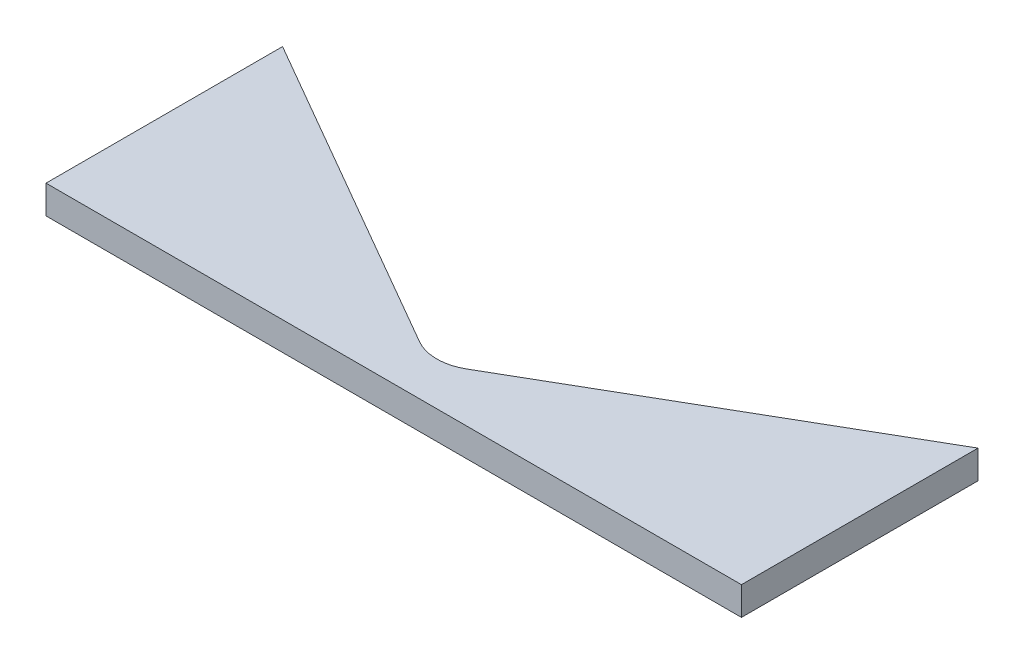
SolidWorks part; units mm, degrees
material "Pine"
ref_plane "Front Plane" through (0, 0, 0) normal (0, 0, 1) x (1, 0, 0)
ref_plane "Top Plane" through (0, 0, 0) normal (0, 1, 0) x (1, 0, 0)
ref_plane "Right Plane" through (0, 0, 0) normal (1, 0, 0) x (0, 0, -1)
sketch "Sketch1" plane through (0, 0, 0) normal (0, 1, 0) x (1, 0, 0)
  line L1 (-233.3625, 0) -> (233.3625, 0)
  line L2 (-233.3625, 0) -> (-233.3625, 158.75)
  line L4 (233.3625, 0) -> (233.3625, 158.75)
  line L6 (0, 0) -> (0, 28.9298) construction
  line L7 (-15.875, 33.1835) -> (-233.3625, 158.75)
  line L8 (233.3625, 158.75) -> (15.875, 33.1835)
  arc A0 (-15.875, 33.1835) -> (15.875, 33.1835) centre (0, 60.6798) ccw
  point P4 (0, 0)
  point P13 (0, 28.9298)
  dimension "D5" = 31.75
  dimension "D1" = 466.725
  dimension "D2" = 158.75
  dimension "D3" = 60
extrude "Boss-Extrude1" add sketch "Sketch1" along normal blind 19.05
